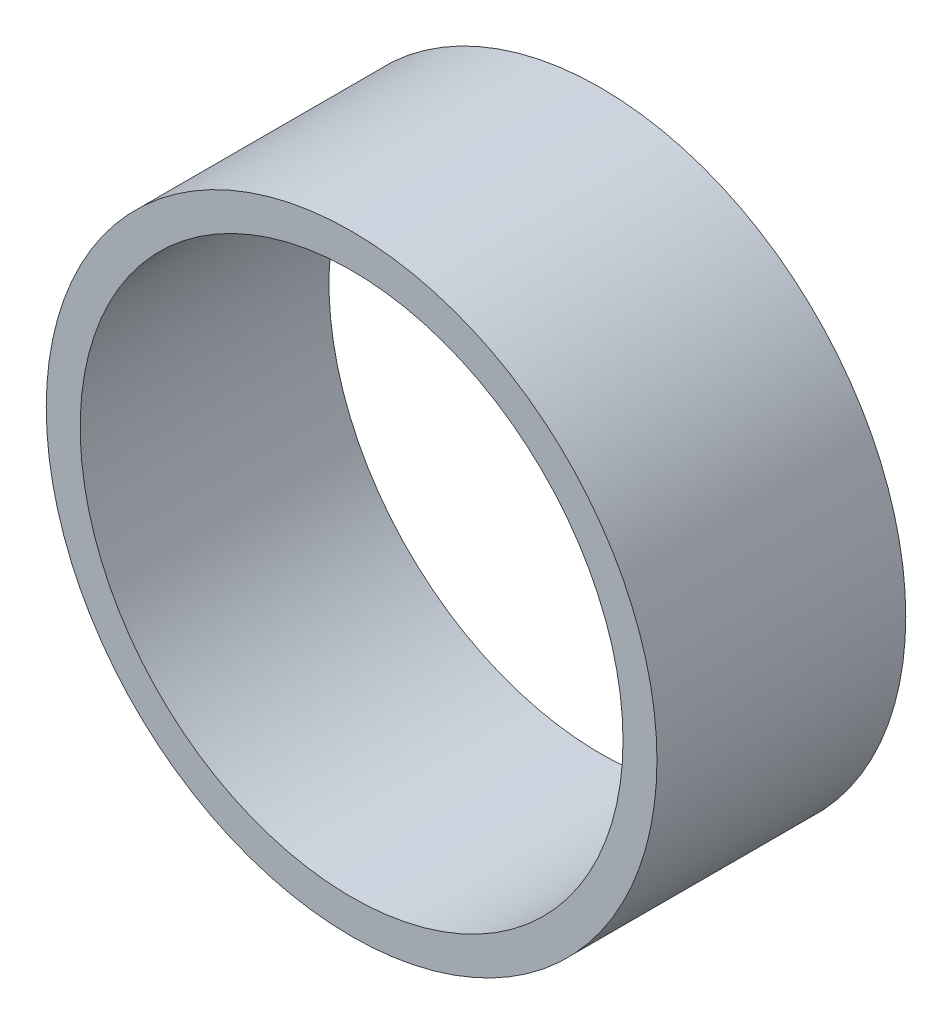
SolidWorks part; units mm, degrees
ref_plane "Front Plane" through (0, 0, 0) normal (0, 0, 1) x (1, 0, 0)
ref_plane "Top Plane" through (0, 0, 0) normal (0, 1, 0) x (1, 0, 0)
ref_plane "Right Plane" through (0, 0, 0) normal (1, 0, 0) x (0, 0, -1)
sketch "Sketch2" plane through (0, 0, 0) normal (0, 0, 1) x (1, 0, 0)
  circle A0 centre (0, 0) radius 67.5
  dimension "D1" = 135
extrude "Boss-Extrude1" add sketch "Sketch2" along normal mid plane 55
sketch "Sketch3" plane through (0, 0, 27.5) normal (0, 0, 1) x (1, 0, 0)
  circle A0 centre (0, 0) radius 60
  dimension "D1" = 120
extrude "Cut-Extrude1" cut sketch "Sketch3" against normal through all contours A0
